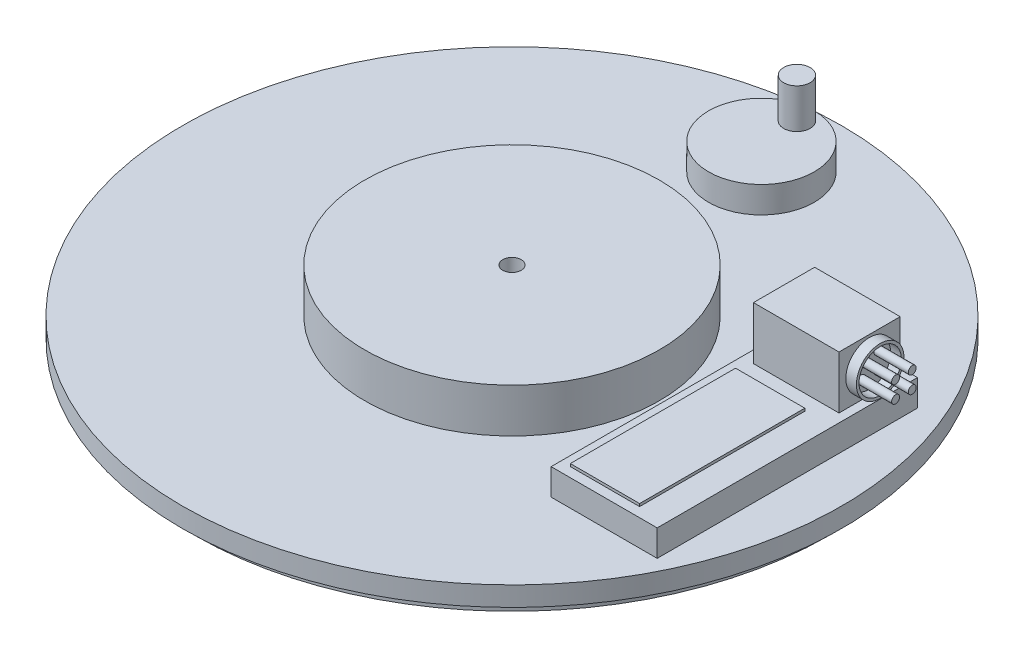
SolidWorks part; units mm, degrees
ref_plane "Front Plane" through (0, 0, 0) normal (0, 0, 1) x (1, 0, 0)
ref_plane "Top Plane" through (0, 0, 0) normal (0, 1, 0) x (1, 0, 0)
ref_plane "Right Plane" through (0, 0, 0) normal (1, 0, 0) x (0, 0, -1)
sketch "Sketch1" plane through (0, 0, 0) normal (1, 0, 0) x (0, 0, -1)
  line L1 (-124.7273, 4.9298) -> (-120, 4.9298)
  line L2 (-120, 4.9298) -> (-120, 0.3182)
  line L3 (-120, 0.3182) -> (-52.5, 0.3182)
  line L4 (-52.5, 0.3182) -> (-52.5, 4.9298)
  line L5 (-52.5, 4.9298) -> (-50.5, 4.9298)
  line L6 (-50.5, 4.9298) -> (-50.5, 12.3182)
  line L7 (-55.7328, 12.3182) -> (-124.7273, 12.3182)
  line L9 (-124.7273, 12.3182) -> (-124.7273, 4.9298)
  line L10 (0, -1000) -> (0, 49000) construction
  line L11 (-3.5, 28.9964) -> (-3.5, 22.6517)
  line L13 (-50.5, 12.3182) -> (-50.5, 22.6517)
  line L14 (-50.5, 28.9964) -> (-55.7328, 28.9964)
  line L15 (-55.7328, 12.3182) -> (-55.7328, 28.9964)
  line L16 (-50.5, 28.9964) -> (-3.5, 28.9964)
  line L18 (-50.5, 22.6517) -> (-3.5, 22.6517)
  dimension "D1" = 2
  dimension "D2" = 52.5
  dimension "D3" = 67.5
  dimension "D4" = 3.5
revolve "Revolve2" add sketch "Sketch1" angle 360 about L10
sketch "Sketch2" plane through (0, 12.3182, 0) normal (0, 1, 0) x (1, 0, 0)
  line L0 (66.8303, 46.4923) -> (66.8303, -52.0184)
  line L1 (66.8303, 46.4923) -> (106.9643, 46.4923)
  line L3 (66.8303, -52.0184) -> (106.9643, -52.0184)
  line L4 (106.9643, 46.4923) -> (106.9643, -52.0184)
  circle A0 centre (0, 94.392) radius 20
  point P2 (70.5805, 18.6204)
extrude "Boss-Extrude1" add sketch "Sketch2" along normal blind 10
sketch "Sketch3" plane through (0, 22.3182, 0) normal (0, 1, 0) x (1, 0, 0)
  line L1 (70.4399, 14.1507) -> (96.6696, 14.1507)
  line L2 (70.4399, 14.1507) -> (70.4399, -48.3743)
  line L3 (70.4399, -48.3743) -> (96.6696, -48.3743)
  line L4 (96.6696, 14.1507) -> (96.6696, -48.3743)
  line L5 (70.4399, 14.1507) -> (96.6696, -48.3743) construction
  line L6 (70.4399, -48.3743) -> (96.6696, 14.1507) construction
  point P0 (83.5548, -17.1118)
extrude "Boss-Extrude2" add sketch "Sketch3" along normal blind 1
sketch "Sketch4" plane through (0, 22.3182, 0) normal (0, 1, 0) x (1, 0, 0)
  circle A0 centre (0, 107.8275) radius 5
extrude "Boss-Extrude3" add sketch "Sketch4" along normal blind 15
sketch "Sketch5" plane through (0, 22.3182, 0) normal (0, 1, 0) x (1, 0, 0)
  line L1 (71.3439, 43.1938) -> (103.7221, 43.1938)
  line L2 (71.3439, 43.1938) -> (71.3439, 20.0343)
  line L3 (71.3439, 20.0343) -> (103.7221, 20.0343)
  line L4 (103.7221, 43.1938) -> (103.7221, 20.0343)
  line L5 (71.3439, 43.1938) -> (103.7221, 20.0343) construction
  line L6 (71.3439, 20.0343) -> (103.7221, 43.1938) construction
  point P0 (87.533, 31.614)
extrude "Boss-Extrude4" add sketch "Sketch5" along normal blind 20
sketch "Sketch6" plane through (103.7221, 0, 0) normal (1, 0, 0) x (0, 0, -1)
  line L0 (20.0343, 42.3182) -> (43.1938, 42.3182) construction
  line L1 (20.0343, 42.3182) -> (20.0343, 22.3182) construction
  circle A0 centre (31.614, 32.3182) radius 9
  circle A1 centre (31.614, 32.3182) radius 8
  point P4 (31.614, 42.3182)
  point P7 (20.0343, 32.3182)
  dimension "D1" = 18
extrude "Boss-Extrude5" add sketch "Sketch6" along normal blind 4
sketch "Sketch7" plane through (103.7221, 0, 0) normal (1, 0, 0) x (0, 0, -1)
  line L0 (31.614, 40.3182) -> (31.614, 24.3182) construction
  line L1 (23.614, 32.3182) -> (39.614, 32.3182) construction
  circle A0 centre (31.614, 32.3182) radius 8 construction
  circle A1 centre (31.614, 32.3182) radius 8 construction
  circle A2 centre (34.7582, 35.527) radius 1.5057
  circle A3 centre (28.4699, 35.527) radius 1.5057
  circle A4 centre (34.7582, 29.1094) radius 1.5057
  circle A5 centre (28.4699, 29.1094) radius 1.5057
extrude "Boss-Extrude6" add sketch "Sketch7" along normal blind 13
